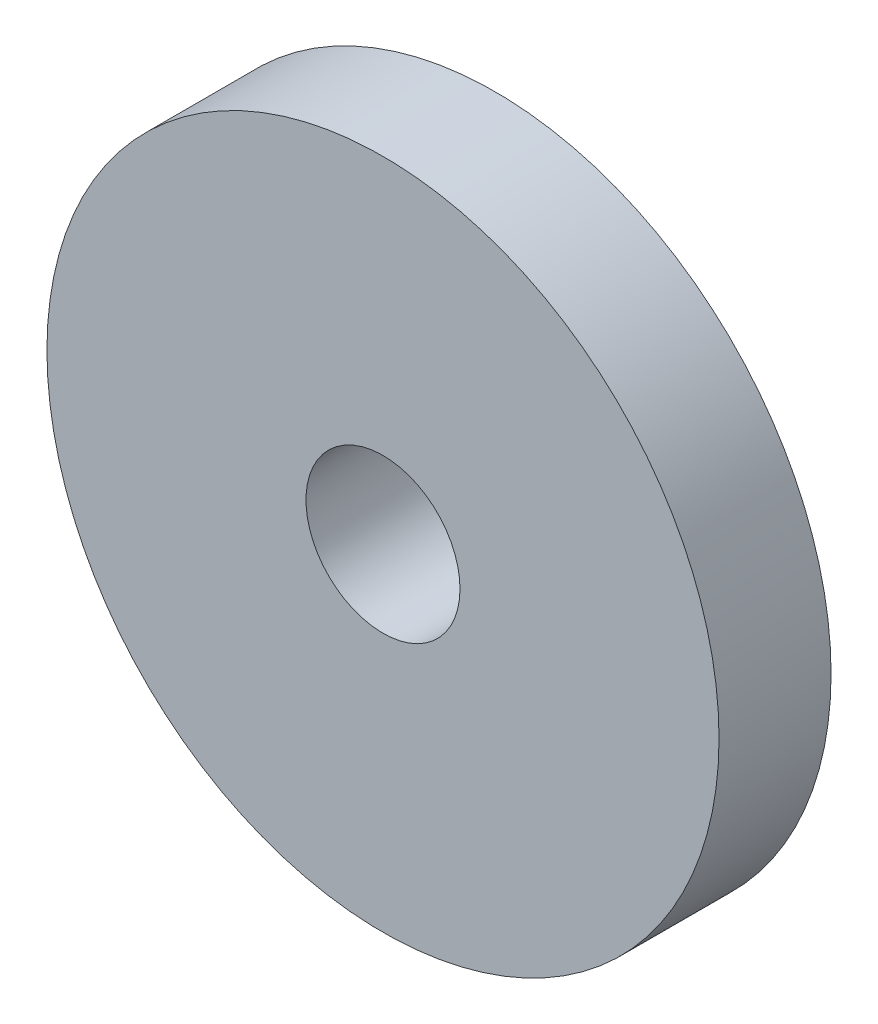
SolidWorks part; units mm, degrees
ref_plane "Front Plane" through (0, 0, 0) normal (0, 0, 1) x (1, 0, 0)
ref_plane "Top Plane" through (0, 0, 0) normal (0, 1, 0) x (1, 0, 0)
ref_plane "Right Plane" through (0, 0, 0) normal (1, 0, 0) x (0, 0, -1)
sketch "Sketch1" plane through (0, 0, 0) normal (0, 0, 1) x (1, 0, 0)
  circle A0 centre (0, 0) radius 6
  circle A1 centre (0, 0) radius 1.375
  dimension "D1" = 12
  dimension "D2" = 2.75
extrude "Boss-Extrude1" add sketch "Sketch1" along normal blind 2
